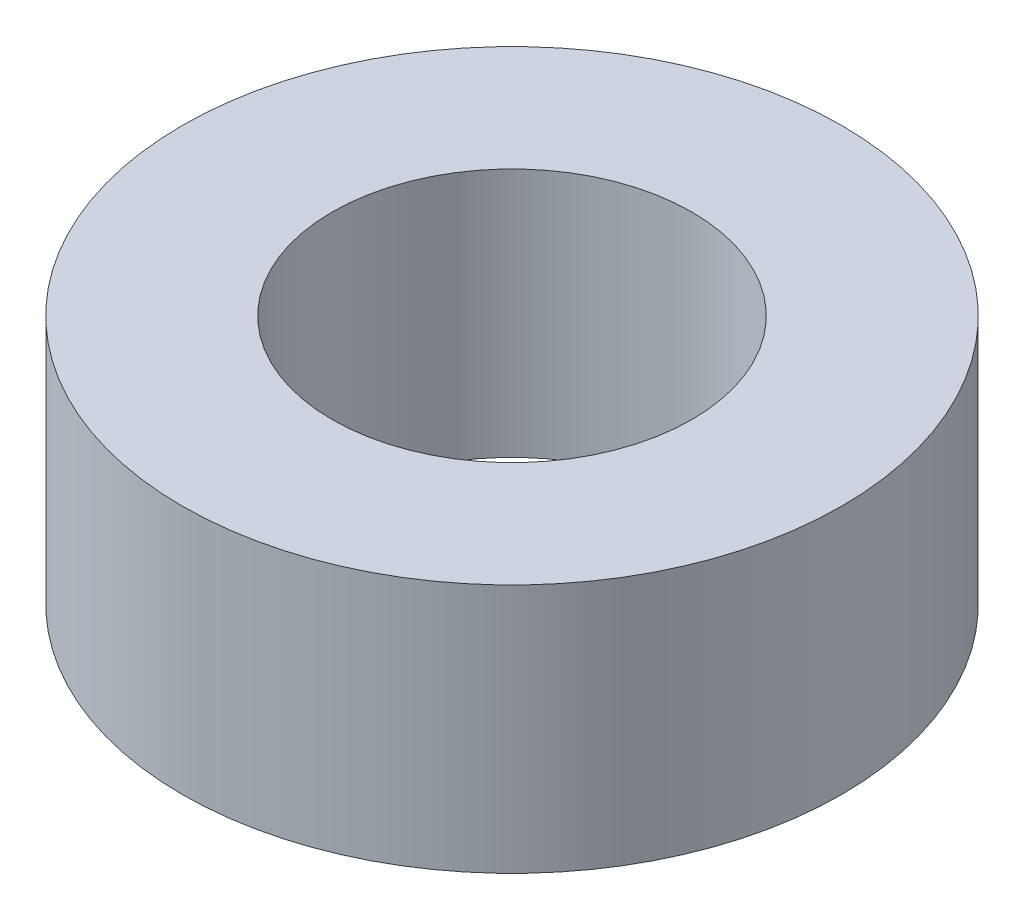
SolidWorks part; units mm, degrees
ref_plane "Front Plane" through (0, 0, 0) normal (0, 0, 1) x (1, 0, 0)
ref_plane "Top Plane" through (0, 0, 0) normal (0, 1, 0) x (1, 0, 0)
ref_plane "Right Plane" through (0, 0, 0) normal (1, 0, 0) x (0, 0, -1)
sketch "Sketch1" plane through (0, 0, 0) normal (0, 1, 0) x (1, 0, 0)
  circle A0 centre (0, 0) radius 1.8
  circle A1 centre (0, 0) radius 3.3
  dimension "D1" = 3.6
  dimension "D2" = 6.6
extrude "Boss-Extrude1" add sketch "Sketch1" along normal blind 2.5
